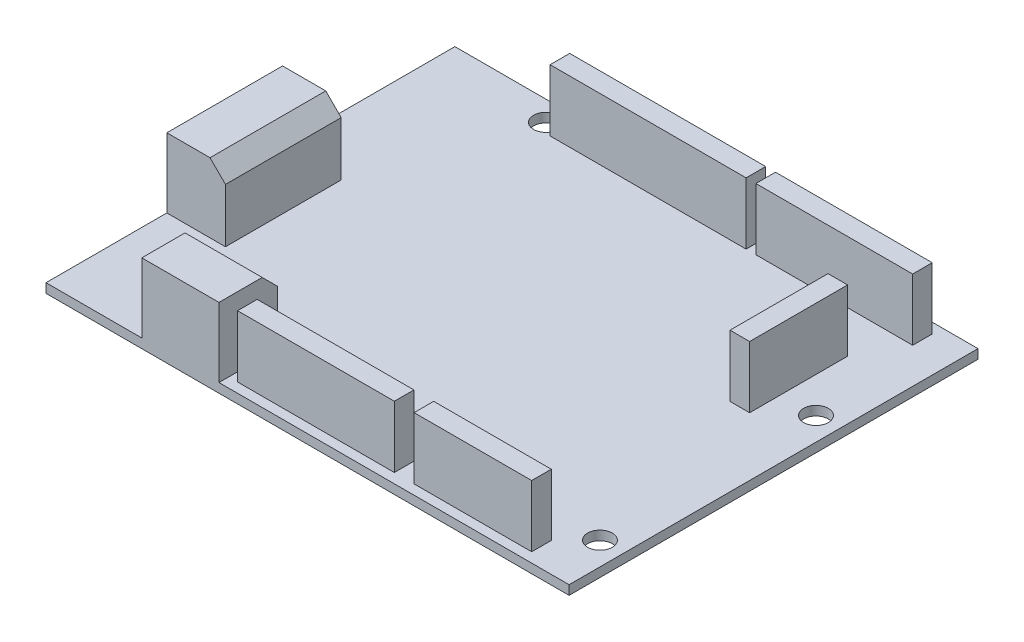
SolidWorks part; units mm, degrees
ref_plane "前视基准面" through (0, 0, 0) normal (0, 0, 1) x (1, 0, 0)
ref_plane "上视基准面" through (0, 0, 0) normal (0, 1, 0) x (1, 0, 0)
ref_plane "右视基准面" through (0, 0, 0) normal (1, 0, 0) x (0, 0, -1)
sketch "草图1" plane through (0, 0, 0) normal (0, 1, 0) x (1, 0, 0)
  line L0 (64.8, 35) -> (64.8, -4.4159) construction
  line L1 (0, 0) -> (67.8, 0)
  line L2 (0, 0) -> (0, 53)
  line L3 (0, 53) -> (67.8, 53)
  line L4 (67.8, 0) -> (67.8, 53)
  circle A0 centre (64.8, 35) radius 1.6
  circle A1 centre (64.8, 7) radius 1.6
  circle A2 centre (14.4, 50.4) radius 1.6
  dimension "D3" = 3.2
  dimension "D4" = 3.2
  dimension "D5" = 3.2
  dimension "D7" = 14.4
  dimension "D10" = 7
  dimension "D1" = 67.8
  dimension "D2" = 53
  dimension "D6" = 28
  dimension "D8" = 2.6
  dimension "D9" = 3
extrude "凸台-拉伸1" add sketch "草图1" along normal blind 1.2
sketch "草图2" plane through (0, 1.2, 0) normal (0, 1, 0) x (1, 0, 0)
  line L0 (67.8, 53) -> (0, 53) construction
  line L1 (16.2, 51.68) -> (41.6, 51.68)
  line L2 (16.2, 51.68) -> (16.2, 49.14)
  line L3 (16.2, 49.14) -> (41.6, 49.14)
  line L4 (41.6, 51.68) -> (41.6, 49.14)
  line L5 (42.87, 51.68) -> (63.19, 51.68)
  line L6 (42.87, 51.68) -> (42.87, 49.14)
  line L7 (42.87, 49.14) -> (63.19, 49.14)
  line L8 (63.19, 51.68) -> (63.19, 49.14)
  line L9 (0, 53) -> (0, 0) construction
  line L10 (67.8, 0) -> (67.8, 53) construction
  line L11 (23.56, 3.81) -> (43.88, 3.81)
  line L12 (23.56, 3.81) -> (23.56, 1.27)
  line L13 (23.56, 1.27) -> (43.88, 1.27)
  line L14 (43.88, 3.81) -> (43.88, 1.27)
  line L15 (46.44, 3.81) -> (61.68, 3.81)
  line L16 (46.44, 3.81) -> (46.44, 1.27)
  line L17 (46.44, 1.27) -> (61.68, 1.27)
  line L18 (61.68, 3.81) -> (61.68, 1.27)
  line L19 (0, 0) -> (67.8, 0) construction
  line L21 (57.66, 43.7) -> (60.2, 43.7)
  line L22 (57.66, 43.7) -> (57.66, 31)
  line L23 (57.66, 31) -> (60.2, 31)
  line L24 (60.2, 43.7) -> (60.2, 31)
  dimension "D1" = 3.86
  dimension "D2" = 2.54
  dimension "D3" = 16.2
  dimension "D4" = 25.4
  dimension "D5" = 1.27
  dimension "D6" = 20.32
  dimension "D7" = 2.54
  dimension "D8" = 6.12
  dimension "D9" = 2.56
  dimension "D10" = 15.24
  dimension "D11" = 20.32
  dimension "D12" = 1.27
  dimension "D13" = 9.3
  dimension "D14" = 2.54
  dimension "D15" = 7.6
  dimension "D16" = 12.7
extrude "凸台-拉伸2" add sketch "草图2" along normal blind 8
sketch "草图3" plane through (0, 1.2, 0) normal (0, 1, 0) x (1, 0, 0)
  line L0 (67.8, 53) -> (0, 53) construction
  line L1 (0, 30.66) -> (7.6, 30.66)
  line L2 (0, 30.66) -> (0, 15.66)
  line L3 (0, 15.66) -> (7.6, 15.66)
  line L4 (7.6, 30.66) -> (7.6, 15.66)
  line L5 (12.42, 7.6) -> (22.42, 7.6)
  line L6 (12.42, 7.6) -> (12.42, 0)
  line L7 (12.42, 0) -> (22.42, 0)
  line L8 (22.42, 7.6) -> (22.42, 0)
  line L10 (0, 53) -> (0, 0) construction
  line L13 (0, 0) -> (67.8, 0) construction
  dimension "D1" = 22.34
  dimension "D2" = 15
  dimension "D3" = 7.6
  dimension "D4" = 7.6
  dimension "D5" = 10
  dimension "D6" = 12.42
extrude "凸台-拉伸3" add sketch "草图3" along normal blind 9
chamfer "倒角1" distance 2 angle 45 2 edges at (17.42, 10.2, -7.6) (7.6, 10.2, -23.16)
